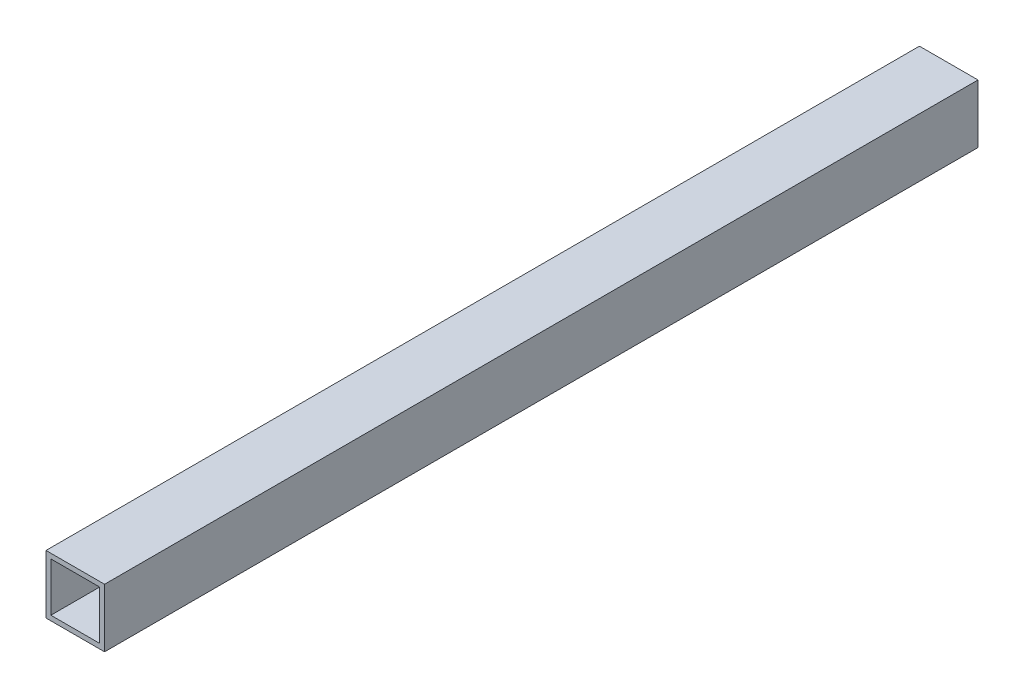
SolidWorks part; units mm, degrees
ref_plane "前视基准面" through (0, 0, 0) normal (0, 0, 1) x (1, 0, 0)
ref_plane "上视基准面" through (0, 0, 0) normal (0, 1, 0) x (1, 0, 0)
ref_plane "右视基准面" through (0, 0, 0) normal (1, 0, 0) x (0, 0, -1)
sketch "草图1" plane through (0, 0, 0) normal (0, 0, 1) x (1, 0, 0)
  line L0 (-12, 12) -> (12, 12)
  line L1 (-10, 10) -> (10, 10)
  line L2 (-10, 10) -> (-10, -10)
  line L3 (-10, -10) -> (10, -10)
  line L4 (10, 10) -> (10, -10)
  line L5 (-10, 10) -> (10, -10) construction
  line L6 (-10, -10) -> (10, 10) construction
  line L7 (12, 12) -> (12, -12)
  line L8 (-12, -12) -> (12, -12)
  line L9 (-12, 12) -> (-12, -12)
  point P0 (0, 0)
  dimension "D1" = 20
  dimension "D2" = 20
  dimension "D3" = 2
extrude "凸台-拉伸1" add sketch "草图1" along normal blind 358
